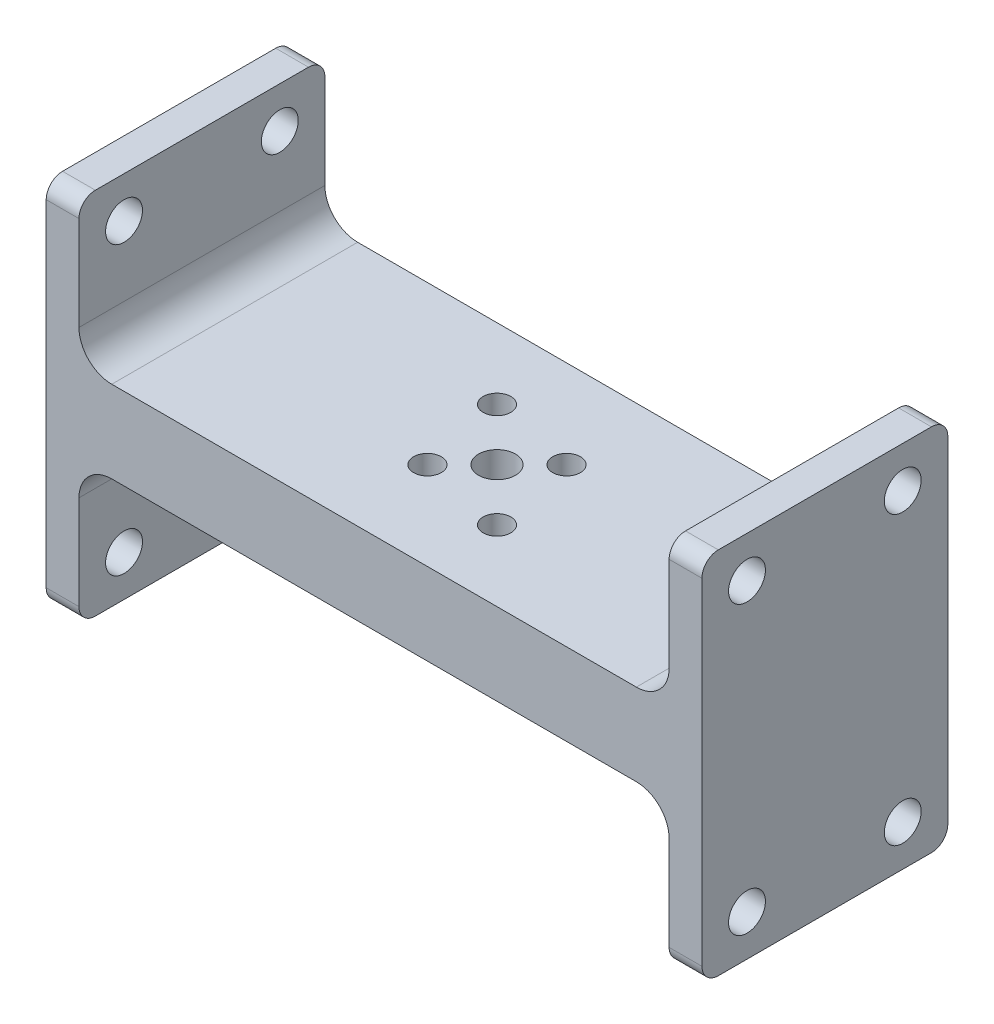
SolidWorks part; units mm, degrees
ref_plane "Front Plane" through (0, 0, 0) normal (0, 0, 1) x (1, 0, 0)
ref_plane "Top Plane" through (0, 0, 0) normal (0, 1, 0) x (1, 0, 0)
ref_plane "Right Plane" through (0, 0, 0) normal (1, 0, 0) x (0, 0, -1)
sketch "Sketch2" plane through (0, 0, 0) normal (0, 1, 0) x (1, 0, 0)
  line L0 (-4.2426, -4.2426) -> (4.2426, 4.2426) construction
  line L1 (-36, 15) -> (36, 15)
  line L2 (-36, 15) -> (-36, -15)
  line L3 (-36, -15) -> (36, -15)
  line L4 (36, 15) -> (36, -15)
  line L5 (6.364, -6.364) -> (-6.364, 6.364) construction
  circle A0 centre (0, 0) radius 2.25
  circle A1 centre (-6.364, 6.364) radius 1.6875
  circle A2 centre (6.364, -6.364) radius 1.6875
  circle A3 centre (4.2426, 4.2426) radius 1.6875
  circle A4 centre (-4.2426, -4.2426) radius 1.6875
  point P4 (0, 15)
  point P6 (-36, 0)
  point P12 (0, 0)
  point P15 (0, 0)
  dimension "D3" = 4.5
  dimension "D8" = 3.375
  dimension "D1" = 72
  dimension "D2" = 30
  dimension "D4" = 90
  dimension "D5" = 45
  dimension "D6" = 18
  dimension "D7" = 12
extrude "Boss-Extrude1" add sketch "Sketch2" along normal blind 10 contours A0 | A1 | L2 L3 L4 L1 | A4 | A3 | A2
sketch "Sketch3" plane through (-36, 0, 0) normal (-1, 0, 0) x (0, 0, 1)
  line L0 (-15, 10) -> (-15, 0) construction
  line L1 (-15, 27.5) -> (15, 27.5)
  line L2 (-15, 27.5) -> (-15, -17.5)
  line L3 (-15, -17.5) -> (15, -17.5)
  line L4 (15, 27.5) -> (15, -17.5)
  line L5 (15, 10) -> (15, 0) construction
  line L6 (-15, 10) -> (-15, 0) construction
  line L7 (0, 27.5) -> (0, -17.5) construction
  circle A0 centre (-9.5, 22.5) radius 2.25
  circle A1 centre (-9.5, -12.5) radius 2.25
  circle A2 centre (9.5, -12.5) radius 2.25
  circle A3 centre (9.5, 22.5) radius 2.25
  point P8 (-15, 5)
  point P9 (-15, 5)
  point P16 (0, 0)
  dimension "D4" = 4.5
  dimension "D5" = 5
  dimension "D1" = 45
  dimension "D2" = 5
  dimension "D3" = 5.5
extrude "Boss-Extrude2" add sketch "Sketch3" along normal blind 4 contours A0 | A3 | A1 | A2 | L2 L3 L4 L1
mirror "Mirror1" about plane through (0, 0, 0) normal (1, 0, 0) of "Boss-Extrude2"
fillet "Fillet1" radius 4 4 edges at (-36, 10, 0) (-36, 0, 0) (36, 0, 0) (36, 10, 0)
fillet "Fillet2" radius 2 8 edges at (38, -17.5, -15) (38, -17.5, 15) (-38, -17.5, -15) (38, 27.5, 15) (38, 27.5, -15) (-38, -17.5, 15) (-38, 27.5, 15) (-38, 27.5, -15)
